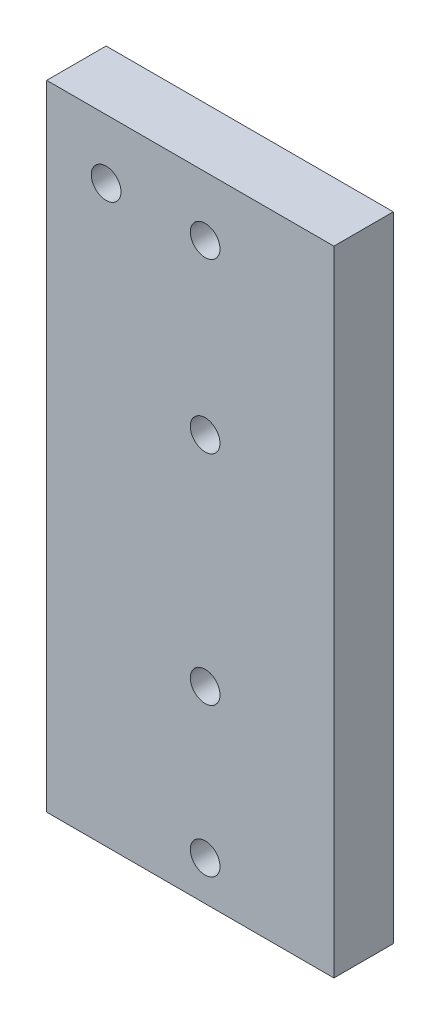
SolidWorks part; units mm, degrees
ref_plane "前视基准面" through (0, 0, 0) normal (0, 0, 1) x (1, 0, 0)
ref_plane "上视基准面" through (0, 0, 0) normal (0, 1, 0) x (1, 0, 0)
ref_plane "右视基准面" through (0, 0, 0) normal (1, 0, 0) x (0, 0, -1)
other "Configuration Table"
sketch "草图1" plane through (0, 0, 0) normal (0, 0, 1) x (1, 0, 0)
  line L1 (-72.5, -160) -> (72.5, -160)
  line L2 (-72.5, -160) -> (-72.5, 160)
  line L3 (-72.5, 160) -> (72.5, 160)
  line L4 (72.5, -160) -> (72.5, 160)
  line L5 (-72.5, -160) -> (72.5, 160) construction
  line L6 (-72.5, 160) -> (72.5, -160) construction
  circle A0 centre (7.5, 130) radius 7.5
  circle A1 centre (-42.5, 130) radius 7.5
  circle A2 centre (7.5, -140) radius 7.5
  circle A3 centre (7.5, 45) radius 7.5
  circle A4 centre (7.5, -65) radius 7.5
  point P0 (0, 0)
  dimension "D3" = 65
  dimension "D5" = 30
  dimension "D6" = 20
  dimension "D7" = 85
  dimension "D9" = 15
  dimension "D10" = 15
  dimension "D11" = 15
  dimension "D12" = 15
  dimension "D13" = 15
  dimension "D1" = 145
  dimension "D2" = 320
  dimension "D4" = 30
  dimension "D8" = 110
extrude "凸台-拉伸1" add sketch "草图1" along normal blind 30
